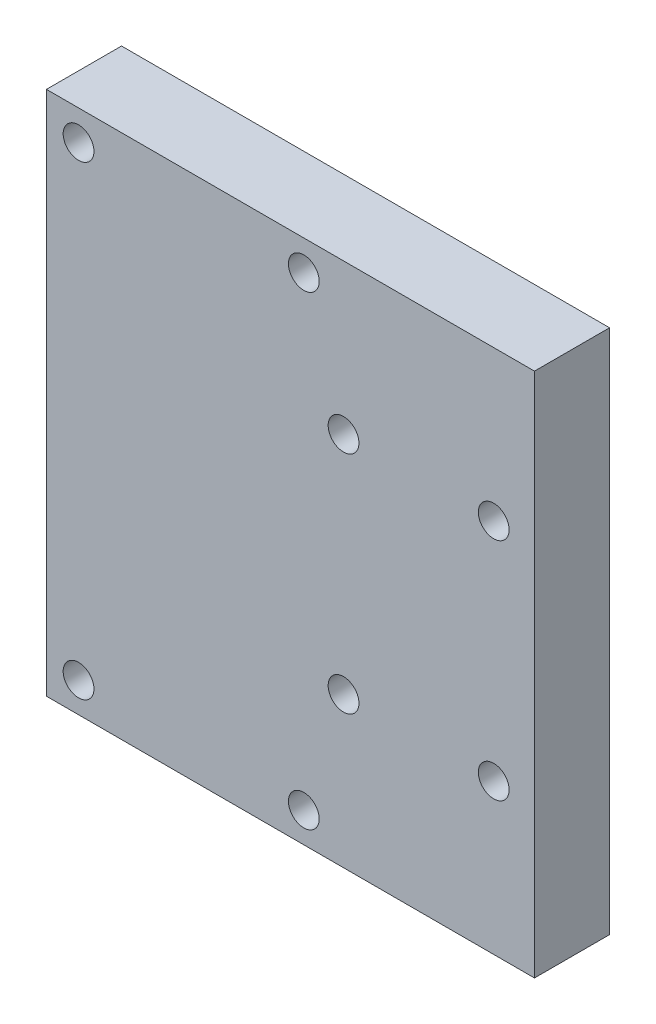
SolidWorks part; units mm, degrees
ref_plane "Front Plane" through (0, 0, 0) normal (0, 0, 1) x (1, 0, 0)
ref_plane "Top Plane" through (0, 0, 0) normal (0, 1, 0) x (1, 0, 0)
ref_plane "Right Plane" through (0, 0, 0) normal (1, 0, 0) x (0, 0, -1)
sketch "Sketch1" plane through (0, 0, 0) normal (0, 0, 1) x (1, 0, 0)
  line L0 (-32.5, 35) -> (32.5, -35) construction
  line L1 (-32.5, 35) -> (32.5, 35)
  line L2 (-32.5, 35) -> (-32.5, -35)
  line L3 (-32.5, -35) -> (32.5, -35)
  line L4 (32.5, 35) -> (32.5, -35)
  line L5 (-13.2216, 0) -> (0, 0) construction
  line L6 (-28.2216, -31) -> (1.7784, -31) construction
  line L7 (-28.2216, -31) -> (-28.2216, 31) construction
  line L8 (-28.2216, 31) -> (1.7784, 31) construction
  line L9 (1.7784, -31) -> (1.7784, 31) construction
  line L10 (-28.2216, -31) -> (1.7784, 31) construction
  line L11 (-28.2216, 31) -> (1.7784, -31) construction
  line L12 (0, 0) -> (17.07, 0) construction
  line L14 (7.07, 15) -> (27.07, 15) construction
  line L15 (7.07, 15) -> (7.07, -15) construction
  line L16 (7.07, -15) -> (27.07, -15) construction
  line L17 (27.07, 15) -> (27.07, -15) construction
  line L18 (7.07, 15) -> (27.07, -15) construction
  line L19 (7.07, -15) -> (27.07, 15) construction
  circle A0 centre (-28.2216, 31) radius 2.05
  circle A1 centre (1.7784, 31) radius 2.05
  circle A2 centre (1.7784, -31) radius 2.05
  circle A3 centre (-28.2216, -31) radius 2.05
  circle A4 centre (27.07, 15) radius 2.05
  circle A5 centre (7.07, 15) radius 2.05
  circle A6 centre (7.07, -15) radius 2.05
  circle A7 centre (27.07, -15) radius 2.05
  point P4 (0, 0)
  dimension "D5" = 4.1
  dimension "D1" = 65
  dimension "D2" = 70
  dimension "D3" = 62
  dimension "D4" = 30
  dimension "D6" = 20
  dimension "D7" = 30
extrude "Boss-Extrude1" add sketch "Sketch1" along normal blind 10
